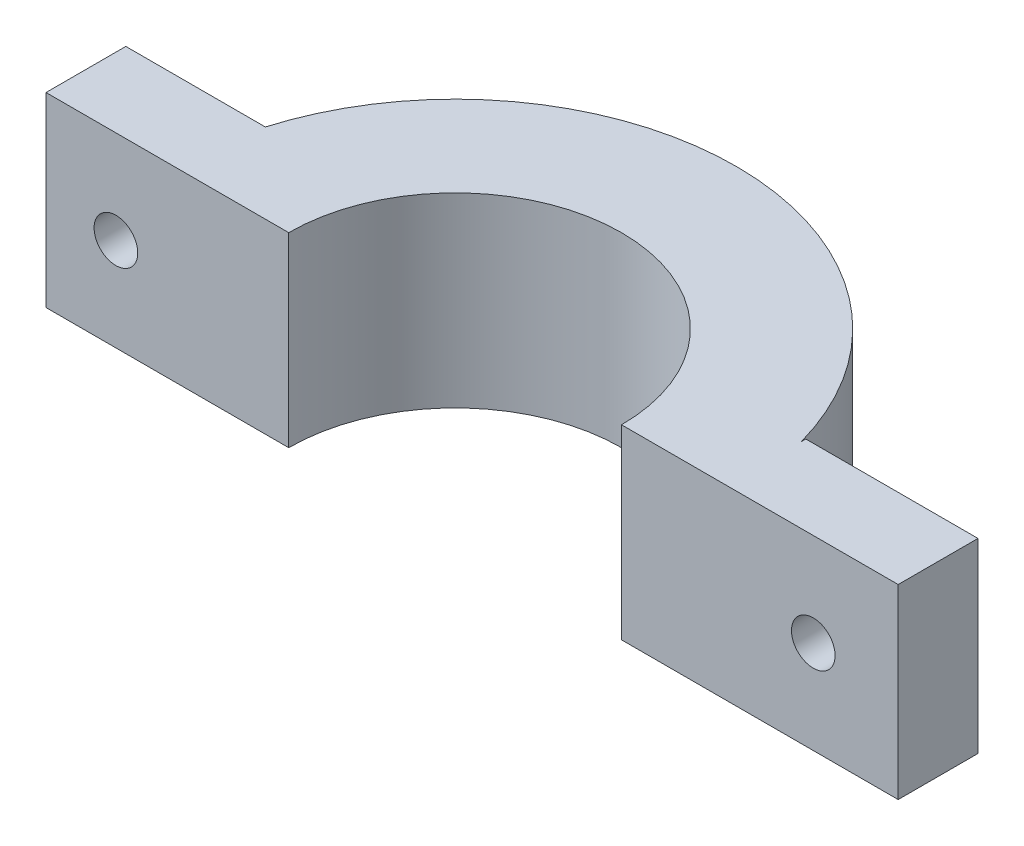
SolidWorks part; units mm, degrees
ref_plane "前基準面" through (0, 0, 0) normal (0, 0, 1) x (1, 0, 0)
ref_plane "上基準面" through (0, 0, 0) normal (0, 1, 0) x (1, 0, 0)
ref_plane "右基準面" through (0, 0, 0) normal (1, 0, 0) x (0, 0, -1)
sketch "草圖1" plane through (0, 0, 0) normal (0, 1, 0) x (1, 0, 0)
  line L1 (-14.255, 7) -> (14.255, 7)
  line L2 (-14.255, 7) -> (-14.255, -7)
  line L3 (-14.255, -7) -> (14.255, -7)
  line L4 (14.255, 7) -> (14.255, -7)
  line L5 (-14.255, 7) -> (14.255, -7) construction
  line L6 (-14.255, -7) -> (14.255, 7) construction
  point P0 (0, 0)
  dimension "D1" = 14
  dimension "D2" = 28.51
extrude "伸長-薄件1" add sketch "草圖1" along normal blind 12.25 thin thin type one direction wall 10
sketch "草圖2" plane through (0, 12.25, 0) normal (0, 1, 0) x (1, 0, 0)
  line L0 (-1014.255, 0) -> (48985.745, 0) construction
  line L1 (-14.255, 7) -> (-14.255, -7) construction
  line L2 (-19.255, -988.4004) -> (-19.255, 49011.5996) construction
  line L3 (-24.255, 17) -> (-19.255, 17) construction
  line L4 (-24.255, 17) -> (-24.255, 11.5996) construction
  line L5 (-24.255, 11.5996) -> (-19.255, 11.5996) construction
  line L6 (-19.255, 17) -> (-19.255, 11.5996) construction
  line L7 (24.255, 17) -> (19.255, 17) construction
  line L8 (24.255, 17) -> (24.255, 12.4477) construction
  line L9 (24.255, 12.4477) -> (19.255, 12.4477) construction
  line L10 (19.255, 17) -> (19.255, 12.4477) construction
  line L11 (19.255, -987.5523) -> (19.255, 49012.4477) construction
  circle A0 centre (-19.255, 0) radius 1.91
  circle A1 centre (19.255, 0) radius 1.91
  point P5 (-14.255, 0)
  dimension "D3" = 3.82
  dimension "D4" = 3.82
  dimension "D1" = 5
  dimension "D2" = 5
extrude "除料-伸長1" cut sketch "草圖2" against normal through all
sketch "草圖4" plane through (0, 0, 0) normal (0, -1, 0) x (1, 0, 0)
  line L0 (-1000, 0) -> (49000, 0) construction
  line L1 (24.255, 17) -> (24.255, -17) construction
  line L2 (11.255, 6.955) -> (24.255, 6.955)
  line L3 (11.255, 6.955) -> (11.255, -6.955)
  line L4 (11.255, -6.955) -> (24.255, -6.955)
  line L5 (24.255, 6.955) -> (24.255, -6.955)
  line L6 (11.255, 6.955) -> (24.255, -6.955) construction
  line L7 (11.255, -6.955) -> (24.255, 6.955) construction
  point P1 (17.755, 0)
  dimension "D1" = 13.91
  dimension "D2" = 13
extrude "填料-伸長1" add sketch "草圖4" along normal blind 74.82
sketch "草圖5" plane through (11.255, 0, 0) normal (-1, 0, 0) x (0, 0, 1)
  line L0 (6.955, -74.82) -> (6.955, 0) construction
  line L1 (-6.955, -74.82) -> (6.955, -74.82)
  line L2 (-6.955, -74.82) -> (-6.955, -58.59)
  line L3 (-6.955, -58.59) -> (6.955, -58.59)
  line L4 (6.955, -74.82) -> (6.955, -58.59)
  dimension "D1" = 16.23
extrude "填料-伸長2" add sketch "草圖5" along normal blind 15
sketch "草圖7" plane through (3.6267, -74.82, 0) normal (0, -1, 0) x (1, 0, 0)
  circle A0 centre (-30.9782, 0) radius 14.5
  dimension "D1" = 29
extrude "伸長-薄件2" add sketch "草圖7" against normal blind 16.23 thin
ref_plane "平面1" through (-60, 0, 0) normal (1, 0, 0) x (0, 0, -1)
sketch "草圖12" plane through (0, 0, -6.955) normal (0, 0, -1) x (-1, 0, 0)
  line L0 (-996.255, -66.705) -> (49003.745, -66.705) construction
  line L1 (3.745, -74.82) -> (3.745, -58.59) construction
  line L2 (-3.755, -1058.59) -> (-3.755, 48941.41) construction
  line L3 (3.745, -58.59) -> (-11.255, -58.59) construction
  circle A0 centre (-3.8567, -66.705) radius 1.9
  point P5 (3.745, -66.705)
  point P10 (-3.755, -58.59)
  dimension "D1" = 3.8
extrude "除料-伸長4" cut sketch "草圖12" against normal through all
ref_plane "平面2" through (-55, 0, 0) normal (1, 0, 0) x (0, 0, -1)
sketch "草圖13" plane through (-55, 0, 0) normal (1, 0, 0) x (0, 0, -1)
  line L1 (6.955, -58.59) -> (-6.955, -58.59)
  line L2 (6.955, -58.59) -> (6.955, -74.82)
  line L3 (6.955, -74.82) -> (-6.955, -74.82)
  line L4 (-6.955, -58.59) -> (-6.955, -74.82)
extrude "填料-伸長3" add sketch "草圖13" along normal blind 10 and the other way blind 8
sketch "草圖14" plane through (0, 0, -6.955) normal (0, 0, -1) x (-1, 0, 0)
  line L0 (-949.1564, -66.705) -> (49050.8436, -66.705) construction
  line L1 (50.8436, -58.59) -> (50.8436, -74.82) construction
  line L2 (56.9218, -1058.59) -> (56.9218, 48941.41) construction
  line L3 (63, -58.59) -> (50.8436, -58.59) construction
  circle A0 centre (56.908, -66.705) radius 1.9
  point P5 (50.8436, -66.705)
  point P10 (56.9218, -58.59)
  dimension "D1" = 3.8
extrude "除料-伸長5" cut sketch "草圖14" against normal through all
sketch "草圖16" plane through (0, 12.25, 0) normal (0, 1, 0) x (1, 0, 0)
  line L0 (-63, 6.955) -> (-63, -6.955) construction
  line L1 (-63, 0) -> (27.7094, 0)
  line L2 (-63, 0) -> (-63, -28.9551)
  line L3 (-63, -28.9551) -> (27.7094, -28.9551)
  line L4 (27.7094, 0) -> (27.7094, -28.9551)
extrude "除料-伸長7" cut sketch "草圖16" against normal through all
sketch "草圖17" plane through (11.255, 0, 0) normal (-1, 0, 0) x (0, 0, 1)
  line L1 (0, -58.59) -> (-20.2305, -58.59)
  line L2 (0, -58.59) -> (0, 22.1336)
  line L3 (0, 22.1336) -> (-20.2305, 22.1336)
  line L4 (-20.2305, -58.59) -> (-20.2305, 22.1336)
sketch "草圖18" plane through (0, 0, 0) normal (0, 0, 1) x (1, 0, 0)
  line L0 (11.255, -58.59) -> (11.255, 22.1336) construction
  line L1 (24.255, -74.82) -> (11.255, -74.82)
  line L2 (24.255, -74.82) -> (24.255, 18.2609)
  line L3 (24.255, 18.2609) -> (11.255, 18.2609)
  line L4 (11.255, -74.82) -> (11.255, 18.2609)
extrude "除料-伸長10" cut sketch "草圖18" against normal blind 27
extrude "除料-伸長11" cut sketch "草圖17" against normal blind 27 and the other way blind 57
